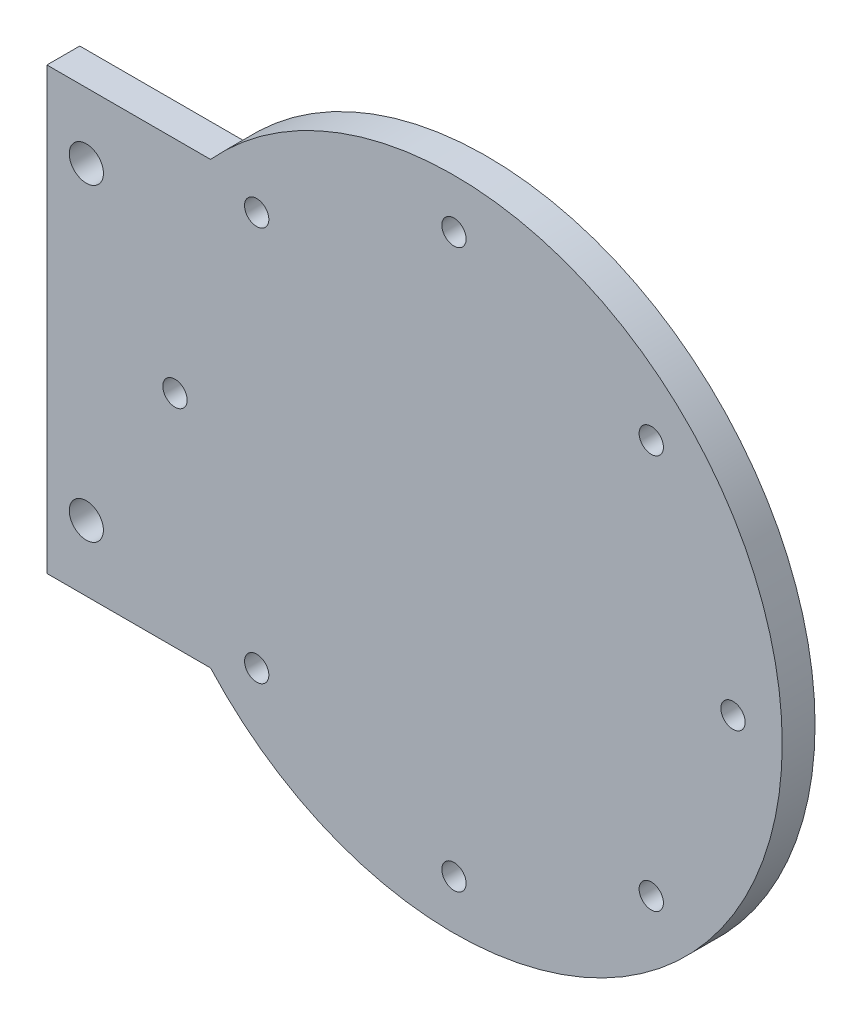
SolidWorks part; units mm, degrees
ref_plane "前视基准面" through (0, 0, 0) normal (0, 0, 1) x (1, 0, 0)
ref_plane "上视基准面" through (0, 0, 0) normal (0, 1, 0) x (1, 0, 0)
ref_plane "右视基准面" through (0, 0, 0) normal (1, 0, 0) x (0, 0, -1)
other "Configuration Table"
sketch "草图1" plane through (0, 0, 0) normal (0, 0, 1) x (1, 0, 0)
  line L4 (-43.8217, -33.8085) -> (-43.8217, 33.2735)
  line L5 (-43.8217, -33.8085) -> (-55.8217, -33.8085)
  line L6 (-55.8217, -33.8085) -> (-55.8217, 33.2735)
  line L7 (-43.8217, 33.2735) -> (-55.8217, 33.2735)
  line L8 (-55.8217, -0.2675) -> (51.7237, -0.2675) construction
  line L9 (-43.8217, 33.2735) -> (-23.8217, 33.2735)
  line L10 (-43.8217, 33.2735) -> (-43.8217, -33.8085)
  line L11 (-43.8217, -33.8085) -> (-23.8217, -33.8085)
  line L12 (-23.8217, 33.2735) -> (-23.8217, -33.8085)
  circle A3 centre (-49.8217, -23.8085) radius 2.6
  circle A4 centre (-49.8217, 23.2735) radius 2.6
  circle A5 centre (6.1783, -0.2675) radius 50
  dimension "D1" = 5.2
  dimension "D9" = 5.2
  dimension "D12" = 100
  dimension "D2" = 6
  dimension "D3" = 12
  dimension "D4" = 67.082
  dimension "D5" = 6
  dimension "D6" = 10
  dimension "D7" = 12
  dimension "D8" = 6
  dimension "D10" = 10
  dimension "D11" = 20
  dimension "D13" = 50
extrude "凸台-拉伸1" add sketch "草图1" along normal blind 5
sketch "草图2" plane through (0, 0, 0) normal (0, 0, -1) x (-1, 0, 0)
  line L3 (30.9027, -33.8085) -> (55.8217, -33.8085)
  line L4 (55.8217, -33.8085) -> (55.8217, 33.2735)
  line L5 (55.8217, 33.2735) -> (30.9027, 33.2735)
  line L6 (30.9027, -33.8085) -> (55.8217, -33.8085)
  line L7 (55.8217, -33.8085) -> (55.8217, 33.2735)
  line L8 (55.8217, 33.2735) -> (30.9027, 33.2735)
  arc A1 (30.9027, 33.2735) -> (30.9027, -33.8085) centre (-6.1783, -0.2675) ccw
  arc A2 (30.9027, 33.2735) -> (30.9027, -33.8085) centre (-6.1783, -0.2675) ccw
  circle A8 centre (36.3217, -0.2675) radius 1.85
  circle A9 centre (23.8737, -30.3195) radius 1.85
  circle A10 centre (-6.1783, -42.7675) radius 1.85
  circle A11 centre (-36.2304, -30.3195) radius 1.85
  circle A12 centre (-48.6783, -0.2675) radius 1.85
  circle A13 centre (-36.2304, 29.7846) radius 1.85
  circle A14 centre (-6.1783, 42.2325) radius 1.85
  circle A15 centre (23.8737, 29.7846) radius 1.85
  point P22 (-6.1783, -0.2675)
  dimension "D2" = 3.7
  dimension "D3" = 42.5
  dimension "D1" = 0
  dimension "D4" = 8
extrude "切除-拉伸1" cut sketch "草图2" against normal blind 10 contours A15 | A8 | A9 | A10 | A11 | A12 | A13 | A14
